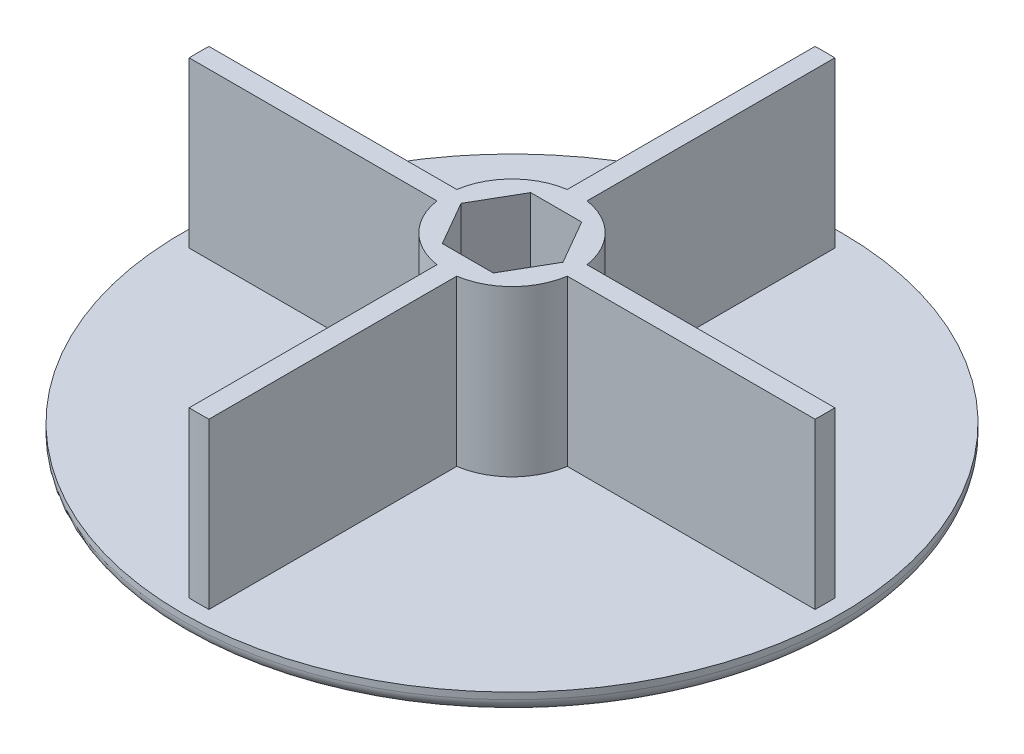
SolidWorks part; units mm, degrees
ref_plane "Plan de face" through (0, 0, 0) normal (0, 0, 1) x (1, 0, 0)
ref_plane "Plan de dessus" through (0, 0, 0) normal (0, 1, 0) x (1, 0, 0)
ref_plane "Plan de droite" through (0, 0, 0) normal (1, 0, 0) x (0, 0, -1)
sketch "Esquisse1" plane through (0, 0, 0) normal (0, 1, 0) x (1, 0, 0)
  circle A0 centre (0, 0) radius 50
  circle A1 centre (0, 0) radius 4.25
  dimension "D1" = 100
  dimension "D2" = 8.5
extrude "Boss.-Extru.1" add sketch "Esquisse1" along normal blind 3
sketch "Esquisse2" plane through (0, 3, 0) normal (0, 1, 0) x (1, 0, 0)
  line L0 (9.8869, 1.5) -> (47.4763, 1.5)
  line L1 (47.4763, -1.5) -> (9.8869, -1.5)
  line L2 (1.5, -9.8869) -> (1.5, -47.4763)
  line L3 (-1.5, -47.4763) -> (-1.5, -9.8869)
  line L4 (-9.8869, -1.5) -> (-47.4763, -1.5)
  line L5 (-47.4763, 1.5) -> (-9.8869, 1.5)
  line L6 (-1.5, 9.8869) -> (-1.5, 47.4763)
  line L7 (1.5, 47.4763) -> (1.5, 9.8869)
  arc A0 (47.4763, 1.5) -> (47.4763, -1.5) centre (0, 0) cw
  arc A1 (9.8869, -1.5) -> (1.5, -9.8869) centre (0, 0) cw
  circle A2 centre (0, 0) radius 4.25 construction
  circle A3 centre (0, 0) radius 4.25
  circle A4 centre (0, 0) radius 50 construction
  arc A5 (1.5, -47.4763) -> (-1.5, -47.4763) centre (0, 0) cw
  arc A6 (-1.5, -9.8869) -> (-9.8869, -1.5) centre (0, 0) cw
  arc A7 (-47.4763, -1.5) -> (-47.4763, 1.5) centre (0, 0) cw
  arc A8 (-9.8869, 1.5) -> (-1.5, 9.8869) centre (0, 0) cw
  arc A9 (-1.5, 47.4763) -> (1.5, 47.4763) centre (0, 0) cw
  arc A10 (1.5, 9.8869) -> (9.8869, 1.5) centre (0, 0) cw
  point P28 (0, 0)
  dimension "D1" = 3
  dimension "D2" = 2.5
  dimension "D3" = 10
  dimension "D4" = 4
extrude "Boss.-Extru.2" add sketch "Esquisse2" along normal blind 25
sketch "Esquisse3" plane through (0, 28, 0) normal (0, 1, 0) x (1, 0, 0)
  line L1 (7.7365, 0) -> (3.8682, 6.7)
  line L2 (3.8682, 6.7) -> (-3.8682, 6.7)
  line L3 (-3.8682, 6.7) -> (-7.7365, 0)
  line L4 (-7.7365, 0) -> (-3.8682, -6.7)
  line L5 (-3.8682, -6.7) -> (3.8682, -6.7)
  line L6 (3.8682, -6.7) -> (7.7365, 0)
  circle A0 centre (0, 0) radius 6.7 construction
  dimension "D1" = 13.4
extrude "Enlèv. mat.-Extru.1" cut sketch "Esquisse3" against normal offset from surface (20 mm away) 8 up to face at (0, 0, 50)
fillet "Congé1" radius 2 2 edges at (0, 0, 4.25) (0, 0, 50)
